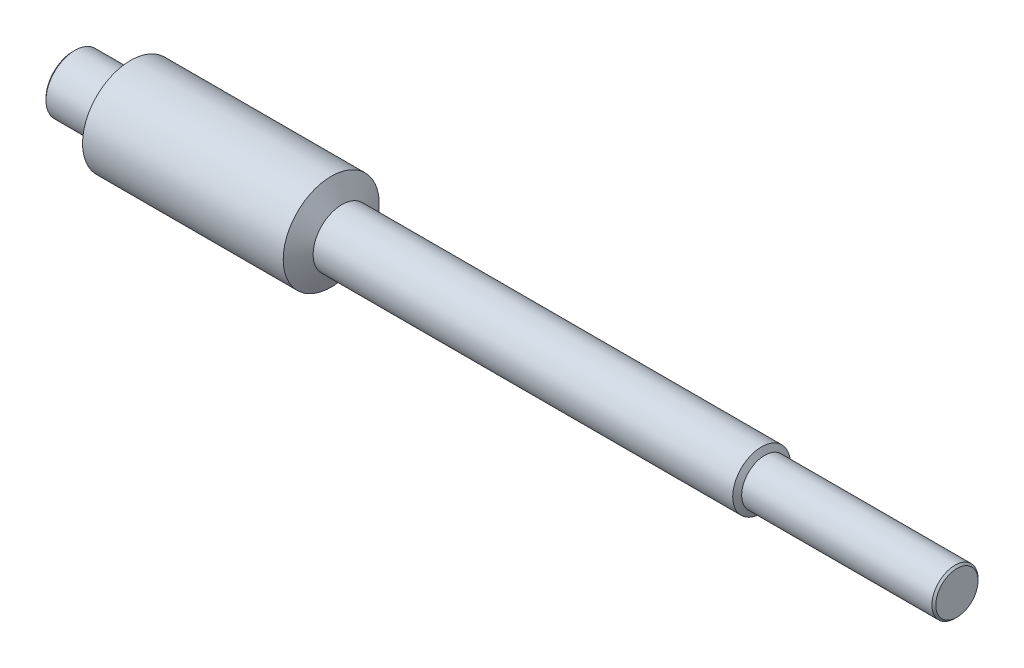
SolidWorks part; units mm, degrees
ref_plane "Płaszczyzna przednia" through (0, 0, 0) normal (0, 0, 1) x (1, 0, 0)
ref_plane "Płaszczyzna górna" through (0, 0, 0) normal (0, 1, 0) x (1, 0, 0)
ref_plane "Płaszczyzna prawa" through (0, 0, 0) normal (1, 0, 0) x (0, 0, -1)
sketch "Szkic1" plane through (0, 0, 0) normal (0, 0, 1) x (1, 0, 0)
  line L0 (-73.1788, 0) -> (85.4113, 0) construction
  line L1 (-133.5223, 0) -> (-133.5223, 15)
  line L2 (-133.5223, 15) -> (-106.5223, 15)
  line L3 (-106.5223, 15) -> (-106.5223, 14)
  line L4 (-106.5223, 14) -> (-103.5223, 14)
  line L5 (-103.5223, 14) -> (-103.5223, 25)
  line L6 (-103.5223, 25) -> (0.9197, 25)
  line L7 (0.9197, 25) -> (6.4777, 15)
  line L8 (6.4777, 15) -> (224.8103, 15)
  line L9 (224.8103, 15) -> (226.4777, 12)
  line L10 (226.4777, 12) -> (326.4777, 12)
  line L11 (326.4777, 12) -> (326.4777, 0)
  line L12 (326.4777, 0) -> (-133.5223, 0)
  dimension "D1" = 30
  dimension "D2" = 30
  dimension "D3" = 3
  dimension "D4" = 1
  dimension "D5" = 50
  dimension "D6" = 24
  dimension "D7" = 30
  dimension "D8" = 110
  dimension "D9" = 320
  dimension "D10" = 100
revolve "Obrót1" add sketch "Szkic1" angle 360 about L0
cosmetic thread "Oznaczenie gwintu1" parameters "D2"=20.704
hole_wizard "Otwór gwintowany M81" positions "Szkic4" profile "Szkic3" tap size "M8" standard "ISO"
sketch "Szkic4" plane through (-133.5223, 0, 0) normal (-1, 0, 0) x (0, 0, 1)
  point P0 (0, 0)
sketch "Szkic3" plane through (-133.5223, 0, 0) normal (0, 1, 0) x (0, 0, 1)
  line L0 (0, 0) -> (0, 14.2929)
  line L1 (0, 14.2929) -> (3.4, 12.25)
  line L2 (3.4, 12.25) -> (3.4, 0)
  line L5 (3.4, 0) -> (0, 0)
  line L10 (0, 14.2929) -> (-3.4, 12.25) construction
  line L11 (0, -6.35) -> (0, 107.95) construction
  dimension "Średnica wiertła gwintu" = 6.8
  dimension "Głębokość otworu gwintowanego" = 12.25
  dimension "Kąt wiertła" = 118
cosmetic thread "Gwint otworu1" parameters "D1"=12.25, "D2"=8
chamfer "Sfazowanie1" distance 1 angle 45 1 edges at (-133.5223, 0, 15)
chamfer "Sfazowanie2" distance 1 angle 45 1 edges at (326.4777, 0, 12)
